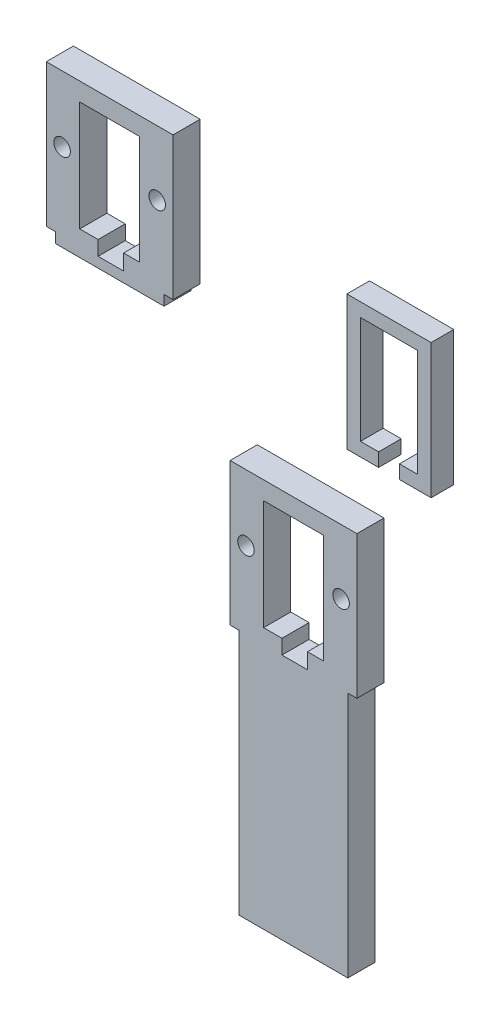
SolidWorks part; units mm, degrees
ref_plane "Front Plane" through (0, 0, 0) normal (0, 0, 1) x (1, 0, 0)
ref_plane "Top Plane" through (0, 0, 0) normal (0, 1, 0) x (1, 0, 0)
ref_plane "Right Plane" through (0, 0, 0) normal (1, 0, 0) x (0, 0, -1)
sketch "Sketch1" plane through (0, 0, 0) normal (0, 0, 1) x (1, 0, 0)
  line L0 (3.7679, -62.8696) -> (-8.2321, -62.8696)
  line L2 (-8.2321, 23.1304) -> (3.7679, 23.1304)
  line L3 (3.7679, 23.1304) -> (15.7679, 23.1304)
  line L5 (15.7679, -62.8696) -> (3.7679, -62.8696)
  line L6 (3.7679, 19.1304) -> (-2.8421, 19.1304)
  line L7 (-2.8421, 19.1304) -> (-2.8421, -5.1596)
  line L10 (10.3779, -4.9196) -> (10.3779, 19.1304)
  line L11 (10.3779, 19.1304) -> (3.7679, 19.1304)
  line L12 (-8.2321, -8.3743) -> (-10.2321, -8.3743)
  line L13 (-10.2321, -8.3743) -> (-10.2321, 23.1304)
  line L14 (-10.2321, 23.1304) -> (-8.2321, 23.1304)
  line L15 (15.7679, -8.3743) -> (17.7679, -8.3743)
  line L16 (17.7679, -8.3743) -> (17.7679, 23.1304)
  line L17 (17.7679, 23.1304) -> (15.7679, 23.1304)
  line L18 (15.7679, -8.3743) -> (15.7679, -62.8696)
  line L19 (-8.2321, -8.3743) -> (-8.2321, -62.8696)
  line L20 (1.2136, -5.1596) -> (1.2136, -8.3743)
  line L21 (1.2136, -8.3743) -> (6.8449, -8.3743)
  line L22 (6.8449, -8.3743) -> (6.8449, -4.9196)
  line L23 (6.8449, -4.9196) -> (10.3779, -4.9196)
  line L24 (1.2136, -5.1596) -> (-2.8421, -5.1596)
  circle A0 centre (-6.7321, 8.5752) radius 1.825
  circle A1 centre (14.2679, 8.8706) radius 1.825
  dimension "D3" = 3.65
  dimension "D8" = 10.5
  dimension "D9" = 21
  dimension "D1" = 24.05
  dimension "D4" = 86
  dimension "D5" = 12
  dimension "D6" = 4
  dimension "D7" = 2
  dimension "D10" = 6.61
extrude "Boss-Extrude1" add sketch "Sketch1" along normal blind 6
sketch "Sketch3" plane through (0, 0, 0) normal (0, 0, 1) x (1, 0, 0)
  line L0 (-36.8447, 45.325) -> (-48.8447, 45.325)
  line L1 (-48.8447, 79.1029) -> (-36.8447, 79.1029)
  line L2 (-36.8447, 79.1029) -> (-24.8447, 79.1029)
  line L3 (-24.8447, 45.325) -> (-36.8447, 45.325)
  line L4 (-36.8447, 75.1029) -> (-43.4497, 75.1029)
  line L5 (-43.4497, 75.1029) -> (-43.4497, 50.8129)
  line L6 (-30.2397, 51.0529) -> (-30.2397, 75.1029)
  line L7 (-30.2397, 75.1029) -> (-36.8447, 75.1029)
  line L8 (-48.8447, 47.5982) -> (-50.8447, 47.5982)
  line L9 (-50.8447, 47.5982) -> (-50.8447, 79.1029)
  line L10 (-50.8447, 79.1029) -> (-48.8447, 79.1029)
  line L11 (-24.8447, 47.5982) -> (-22.8447, 47.5982)
  line L12 (-22.8447, 47.5982) -> (-22.8447, 79.1029)
  line L13 (-22.8447, 79.1029) -> (-24.8447, 79.1029)
  line L14 (-24.8447, 47.5982) -> (-24.8447, 45.325)
  line L15 (-48.8447, 47.5982) -> (-48.8447, 45.325)
  line L16 (-39.394, 50.8129) -> (-39.394, 47.5982)
  line L17 (-39.394, 47.5982) -> (-33.7627, 47.5982)
  line L18 (-33.7627, 47.5982) -> (-33.7627, 51.0529)
  line L19 (-33.7627, 51.0529) -> (-30.2397, 51.0529)
  line L20 (-39.394, 50.8129) -> (-43.4497, 50.8129)
  circle A0 centre (-47.3447, 64.5477) radius 1.825
  circle A1 centre (-26.3447, 64.8431) radius 1.825
  dimension "D2" = 3.65
  dimension "D1" = 24.05
  dimension "D4" = 12
  dimension "D5" = 4
  dimension "D6" = 10.5
  dimension "D7" = 21
  dimension "D8" = 6.605
  dimension "D9" = 2
extrude "Boss-Extrude2" add sketch "Sketch3" along normal blind 6 separate body
sketch "Sketch4" plane through (0, 0, 0) normal (0, 0, 1) x (1, 0, 0)
  line L0 (14.5591, 66.879) -> (33.1591, 66.879)
  line L1 (33.1591, 66.879) -> (33.1591, 37.179)
  line L2 (33.1591, 37.179) -> (26.1591, 37.179)
  line L3 (26.1591, 37.179) -> (26.1591, 40.179)
  line L4 (26.1591, 40.179) -> (30.1591, 40.179)
  line L5 (30.1591, 40.179) -> (30.1591, 63.879)
  line L6 (30.1591, 63.879) -> (17.5591, 63.879)
  line L7 (17.5591, 63.879) -> (17.5591, 40.179)
  line L8 (17.5591, 40.179) -> (21.5591, 40.179)
  line L9 (21.5591, 40.179) -> (21.5591, 37.179)
  line L10 (21.5591, 37.179) -> (14.5591, 37.179)
  line L11 (14.5591, 37.179) -> (14.5591, 66.879)
  dimension "D1" = 3
  dimension "D2" = 4
  dimension "D3" = 3
  dimension "D4" = 3
  dimension "D5" = 12.6
  dimension "D6" = 23.7
extrude "Boss-Extrude3" add sketch "Sketch4" along normal blind 5 separate body
